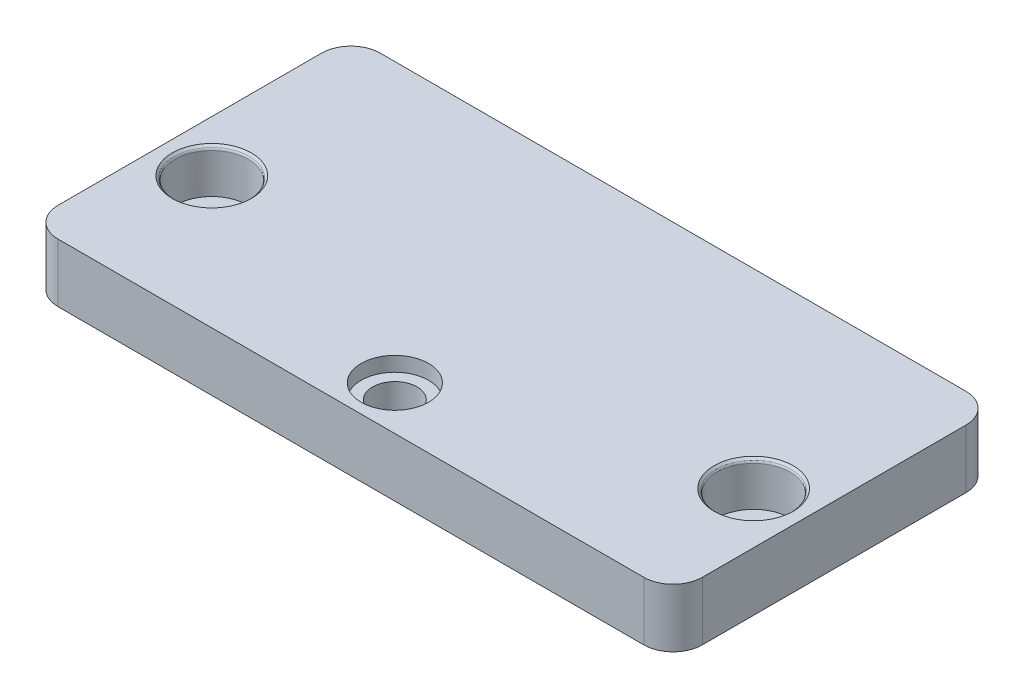
SolidWorks part; units mm, degrees
ref_plane "Front Plane" through (0, 0, 0) normal (0, 0, 1) x (1, 0, 0)
ref_plane "Top Plane" through (0, 0, 0) normal (0, 1, 0) x (1, 0, 0)
ref_plane "Right Plane" through (0, 0, 0) normal (1, 0, 0) x (0, 0, -1)
sketch "Sketch1" plane through (0, 0, 0) normal (0, 1, 0) x (1, 0, 0)
  line L1 (0, 0) -> (220, 0)
  line L2 (0, 0) -> (0, 110)
  line L3 (0, 110) -> (220, 110)
  line L4 (220, 0) -> (220, 110)
  dimension "D1" = 220
  dimension "D2" = 110
extrude "Boss-Extrude1" add sketch "Sketch1" along normal blind 20
sketch "Sketch2" plane through (0, 20, 0) normal (0, 1, 0) x (1, 0, 0)
  line L0 (0, 45) -> (220, 45) construction
  line L1 (0, 110) -> (0, 0) construction
  line L2 (220, 0) -> (220, 110) construction
  line L3 (0, 0) -> (220, 0) construction
  line L4 (110, 45) -> (110, 110) construction
  line L5 (220, 110) -> (0, 110) construction
  circle A0 centre (17.5, 45) radius 12.5
  circle A1 centre (202.5, 45) radius 12.5
  circle A2 centre (110, 15) radius 7.6
  point P10 (110, 45)
  dimension "D2" = 25
  dimension "D4" = 15
  dimension "D5" = 15.2
  dimension "D1" = 45
  dimension "D3" = 92.5
extrude "Cut-Extrude1" cut sketch "Sketch2" against normal blind 15
chamfer "Chamfer1" distance 1 angle 45 2 edges at (202.5, 20, -57.5) (17.5, 20, -32.5)
fillet "Fillet1" radius 1 2 edges at (202.5, 19, -57.5) (17.5, 19, -57.5)
sketch "Sketch4" plane through (0, 20, 0) normal (0, 1, 0) x (1, 0, 0)
  circle A0 centre (110, 15) radius 11.5
  dimension "D1" = 23
extrude "Cut-Extrude2" cut sketch "Sketch4" against normal blind 5
fillet "Fillet2" radius 10 4 edges at (220, 10, -110) (220, 10, 0) (0, 10, 0) (0, 10, -110)
